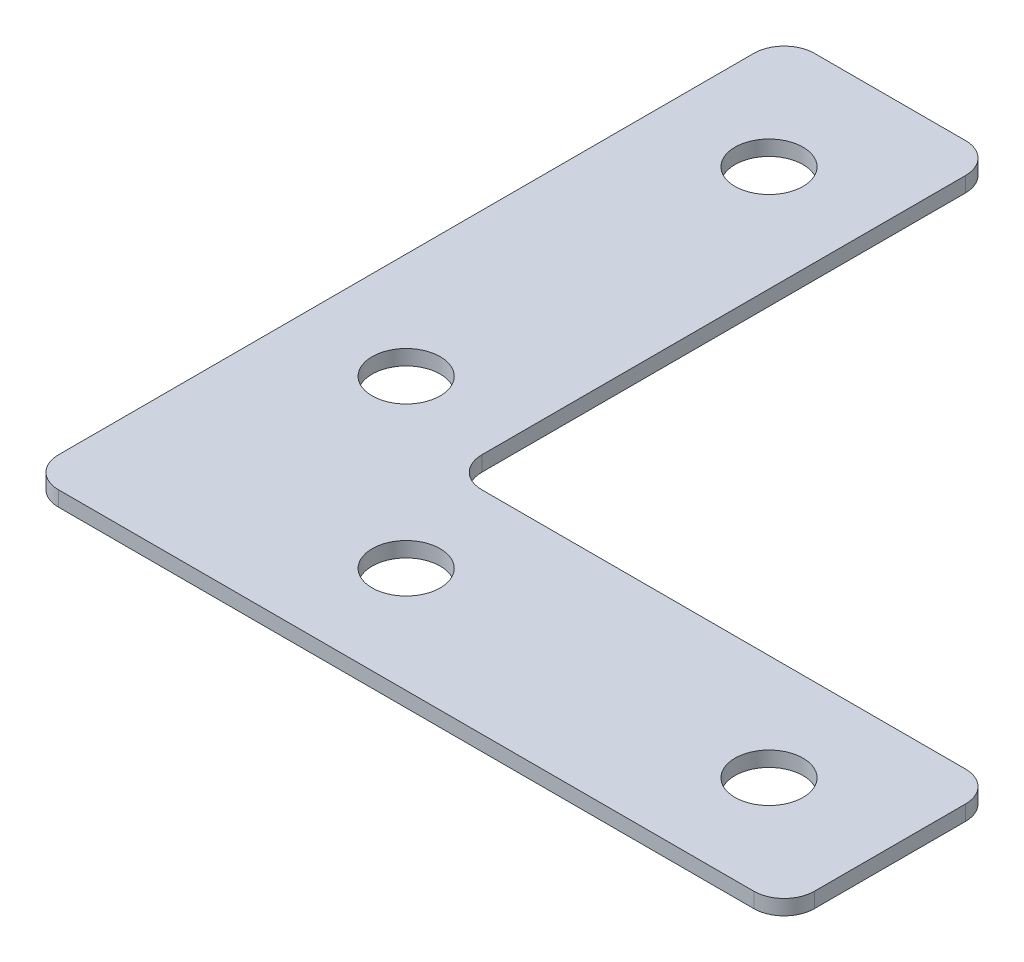
SolidWorks part; units mm, degrees
material "AISI 1020 钢，冷轧"
ref_plane "前视基准面" through (0, 0, 0) normal (0, 0, 1) x (1, 0, 0)
ref_plane "上视基准面" through (0, 0, 0) normal (0, 1, 0) x (1, 0, 0)
ref_plane "右视基准面" through (0, 0, 0) normal (1, 0, 0) x (0, 0, -1)
sketch "草图1" plane through (0, 0, 0) normal (0, 1, 0) x (1, 0, 0)
  line L0 (2, 50) -> (12, 50)
  line L1 (2, 0) -> (48, 0)
  line L2 (0, 2) -> (0, 48)
  line L3 (0, 50) -> (50, 50) construction
  line L4 (50, 0) -> (50, 50) construction
  line L5 (14, 48) -> (14, 16)
  line L6 (16, 14) -> (48, 14)
  line L7 (50, 12) -> (50, 2)
  line L8 (7, 50) -> (7, -0.5648) construction
  line L9 (0, 7) -> (50, 7) construction
  line L10 (0, 7) -> (18, 7) construction
  line L11 (18, 7) -> (42, 7) construction
  line L12 (7, 50) -> (7, 42) construction
  line L13 (7, 42) -> (7, 18) construction
  circle A0 centre (18, 7) radius 2.25
  circle A1 centre (42, 7) radius 2.25
  circle A3 centre (7, 18) radius 2.25
  circle A4 centre (7, 42) radius 2.25
  arc A5 (0, 48) -> (2, 50) centre (2, 48) cw
  arc A6 (12, 50) -> (14, 48) centre (12, 48) cw
  arc A7 (14, 16) -> (16, 14) centre (16, 16) ccw
  arc A8 (2, 0) -> (0, 2) centre (2, 2) cw
  arc A9 (48, 0) -> (50, 2) centre (48, 2) ccw
  arc A10 (48, 14) -> (50, 12) centre (48, 12) cw
  point P8 (50, 7)
  point P9 (0, 7)
  point P10 (7, 50)
  point P11 (7, 0)
  point P29 (14, 50)
  point P34 (0, 0)
  point P40 (50, 14)
  dimension "D6" = 4.5
  dimension "D8" = 4.5
  dimension "D11" = 4.5
  dimension "D12" = 4.5
  dimension "D13" = 2
  dimension "D14" = 2
  dimension "D15" = 2
  dimension "D16" = 2
  dimension "D17" = 2
  dimension "D18" = 2
  dimension "D1" = 50
  dimension "D2" = 50
  dimension "D3" = 14
  dimension "D4" = 14
  dimension "D5" = 18
  dimension "D7" = 24
  dimension "D9" = 8
  dimension "D10" = 24
extrude "凸台-拉伸2" add sketch "草图1" along normal blind 1
